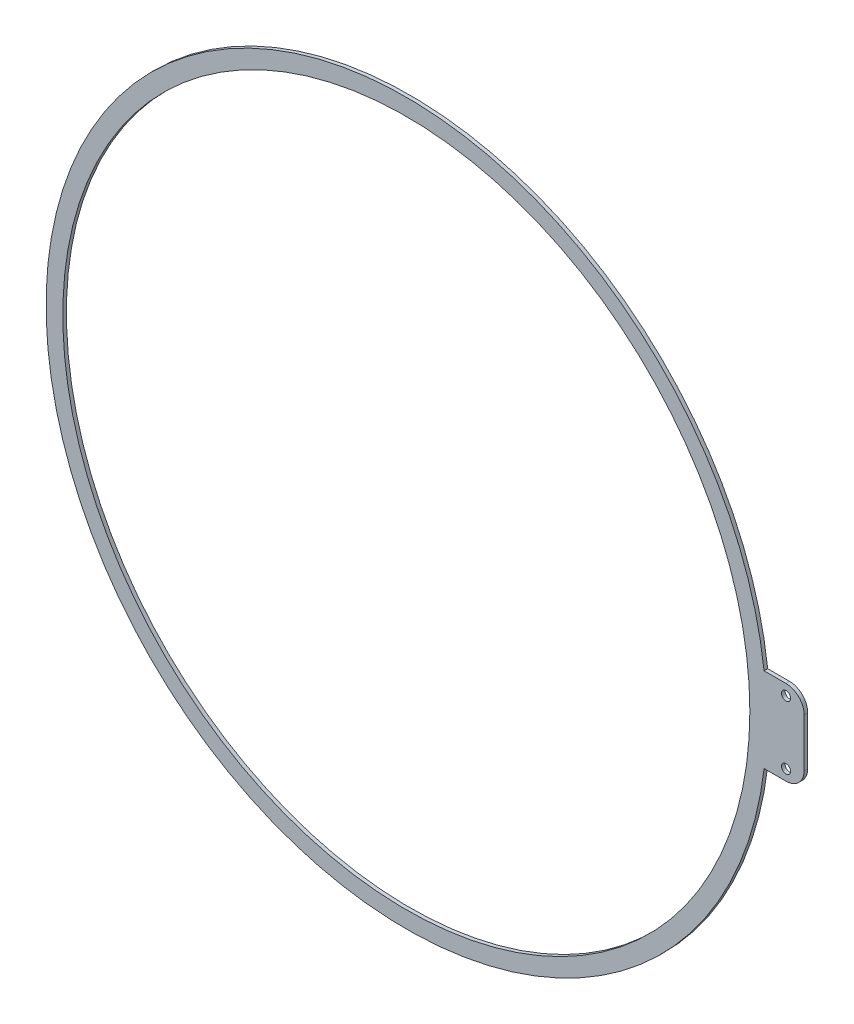
SolidWorks part; units mm, degrees
ref_plane "Front Plane" through (0, 0, 0) normal (0, 0, 1) x (1, 0, 0)
ref_plane "Top Plane" through (0, 0, 0) normal (0, 1, 0) x (1, 0, 0)
ref_plane "Right Plane" through (0, 0, 0) normal (1, 0, 0) x (0, 0, -1)
sketch "Sketch1" plane through (0, 0, 0) normal (0, 0, 1) x (1, 0, 0)
  line L0 (0.9141, 0) -> (50000.9141, 0) construction
  line L1 (99.6208, 0) -> (99.6208, -50000) construction
  line L2 (98.9307, 11.7056) -> (105, 11.7056)
  line L3 (99.5969, 2.1822) -> (110, -11.7056) construction
  line L5 (94.2761, -11.7056) -> (105, -11.7056)
  line L6 (110, 6.7056) -> (110, -6.7056)
  line L7 (97.5, 8.1075) -> (122.5, -8.1075) construction
  line L8 (97.5, 8.1075) -> (122.5, -8.1075) construction
  line L11 (99.5969, -2.1822) -> (110, 11.7056) construction
  circle A0 centre (0, 0) radius 95
  circle A1 centre (0, 0) radius 99.6208
  circle A2 centre (105, 8.75) radius 1.25
  circle A3 centre (105, -8.75) radius 1.25
  arc A4 (105, -11.7056) -> (110, -6.7056) centre (105, -6.7056) ccw
  arc A5 (110, 6.7056) -> (105, 11.7056) centre (105, 6.7056) ccw
  point P8 (110, 0)
  point P13 (101.2315, 0)
  dimension "D1" = 8.75
  dimension "D8" = 5
  dimension "D2" = 110
  dimension "D3" = 8.75
  dimension "D4" = 105
  dimension "D5" = 105
  dimension "D6" = 0
  dimension "D7" = 110
extrude "Boss-Extrude1" add sketch "Sketch1" along normal blind 1
